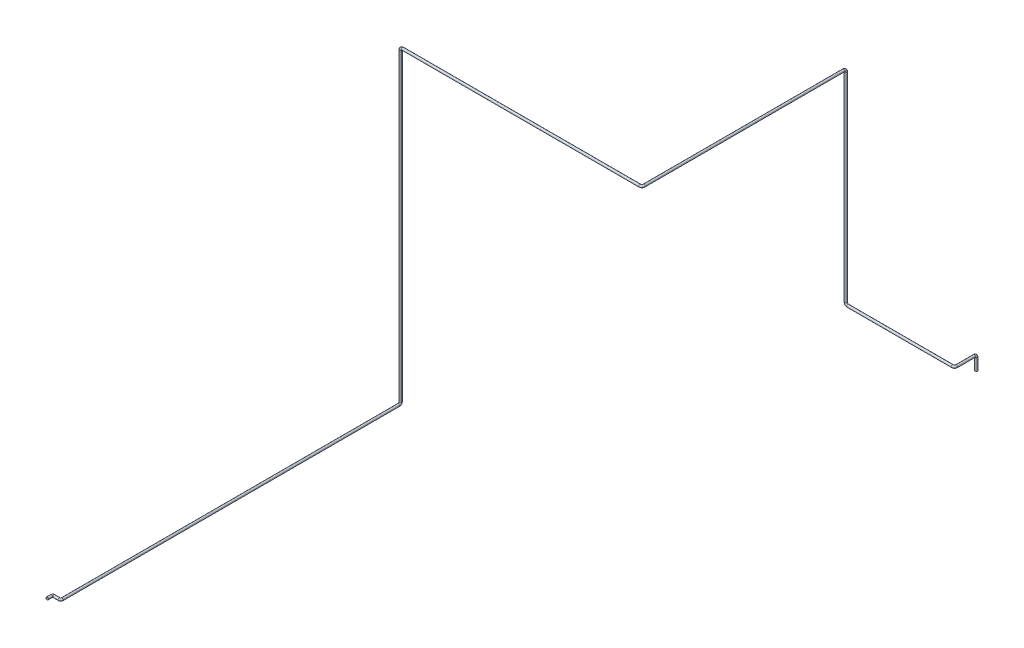
SolidWorks part; units mm, degrees
ref_plane "Alzado" through (0, 0, 0) normal (0, 0, 1) x (1, 0, 0)
ref_plane "Planta" through (0, 0, 0) normal (0, 1, 0) x (1, 0, 0)
ref_plane "Vista lateral" through (0, 0, 0) normal (1, 0, 0) x (0, 0, -1)
sketch "Croquis1" plane through (0, 0, 0) normal (0, 0, 1) x (1, 0, 0)
  circle A0 centre (0, 0) radius 17.5
  dimension "D1" = 35
extrude "Saliente-Extruir1" add sketch "Croquis1" against normal blind 30
sketch3d "Croquis3D1"
  line L0 (0, 0, -30) -> (0, 0, -60)
  line L1 (0, 0, -30) -> (0, 0, 0) construction
  line L2 (20, 0, -80) -> (100, 0, -80)
  line L3 (120, 0, -100) -> (120, 0, -5050)
  line L4 (120, 30, -5080) -> (120, 4510, -5080)
  line L5 (150, 4540, -5080) -> (3640, 4540, -5080)
  line L6 (3670, 4540, -5110) -> (3670, 4540, -8050)
  line L7 (3670, 4510, -8080) -> (3670, 1570, -8080)
  line L8 (3700, 1540, -8080) -> (5240, 1540, -8080)
  line L9 (5270, 1540, -8110) -> (5270, 1540, -8370)
  line L10 (5270, 1510, -8400) -> (5270, 1340, -8400)
  arc A0 (100, 0, -80) -> (120, 0, -100) centre (100, 0, -100) ccw
  arc A1 (0, 0, -60) -> (20, 0, -80) centre (20, 0, -60) ccw
  arc A2 (120, 4510, -5080) -> (150, 4540, -5080) centre (150, 4510, -5080) ccw
  arc A3 (120, 0, -5050) -> (120, 30, -5080) centre (120, 30, -5050) ccw
  arc A4 (3670, 4540, -8050) -> (3670, 4510, -8080) centre (3670, 4510, -8050) ccw
  arc A5 (3640, 4540, -5080) -> (3670, 4540, -5110) centre (3640, 4540, -5110) ccw
  arc A6 (5270, 1540, -8370) -> (5270, 1510, -8400) centre (5270, 1510, -8370) ccw
  arc A7 (5240, 1540, -8080) -> (5270, 1540, -8110) centre (5240, 1540, -8110) ccw
  arc A8 (3670, 1570, -8080) -> (3700, 1540, -8080) centre (3700, 1570, -8080) ccw
  point P15 (120, 0, -80)
  point P16 (100, 20, -100)
  point P19 (0, 0, -80)
  point P20 (20, -20, -60)
  point P23 (120, 4540, -5080)
  point P24 (150, 4510, -5110)
  point P27 (120, 0, -5080)
  point P28 (150, 30, -5050)
  point P31 (3670, 4540, -8080)
  point P32 (3640, 4510, -8050)
  point P35 (3670, 4540, -5080)
  point P36 (3640, 4570, -5110)
  point P39 (5270, 1540, -8400)
  point P40 (5240, 1510, -8370)
  point P43 (5270, 1540, -8080)
  point P44 (5240, 1570, -8110)
  point P47 (3670, 1540, -8080)
  point P48 (3700, 1570, -8050)
  dimension "D11" = 20
  dimension "D12" = 30
  dimension "D13" = 30
  dimension "D14" = 30
  dimension "D1" = 50
  dimension "D2" = 120
  dimension "D3" = 5000
  dimension "D4" = 4540
  dimension "D5" = 3550
  dimension "D6" = 3000
  dimension "D7" = 3000
  dimension "D8" = 1600
  dimension "D9" = 320
  dimension "D10" = 200
sketch "Croquis2" plane through (0, 0, -30) normal (0, 0, -1) x (-1, 0, 0)
  circle A0 centre (0, 0) radius 17.5
  dimension "D1" = 35
sweep "Barrer1" add profiles "Croquis2" path "Croquis3D1"
